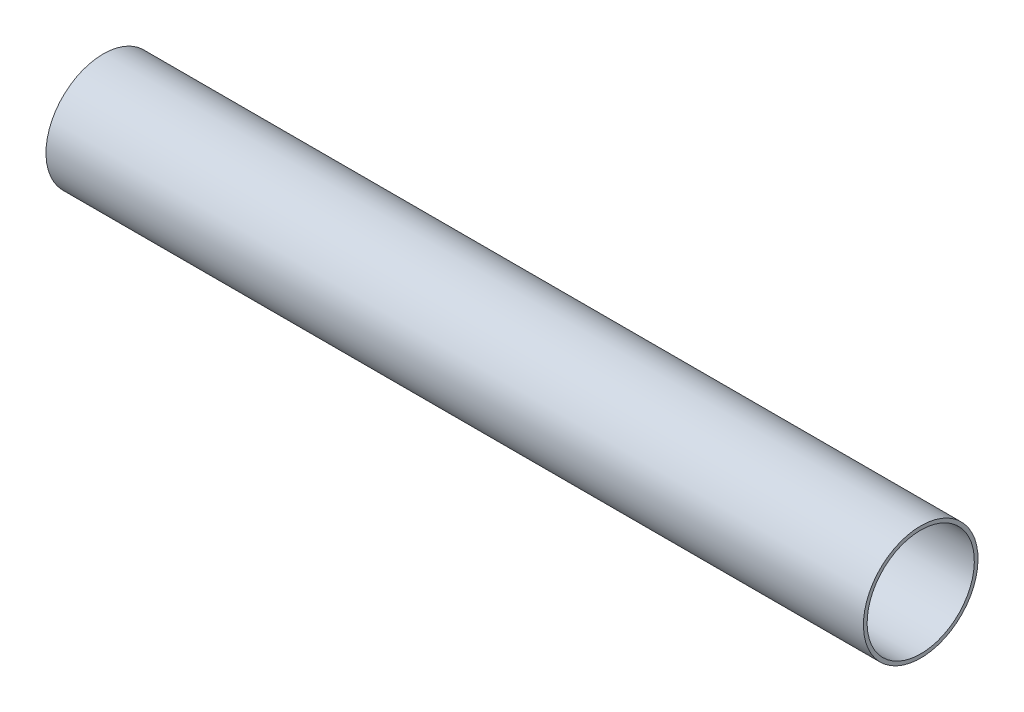
SolidWorks part; units mm, degrees
material "1060 Alloy"
ref_plane "Front Plane" through (0, 0, 0) normal (0, 0, 1) x (1, 0, 0)
ref_plane "Top Plane" through (0, 0, 0) normal (0, 1, 0) x (1, 0, 0)
ref_plane "Right Plane" through (0, 0, 0) normal (1, 0, 0) x (0, 0, -1)
sketch "Sketch1" plane through (0, 0, 0) normal (0, 0, 1) x (1, 0, 0)
  line L1 (0, 0) -> (-702.056, 0) construction
  line L2 (0, 0) -> (0, 49.2125) construction
  line L3 (0, 49.2125) -> (-702.056, 49.2125) construction
  line L4 (-702.056, 0) -> (-702.056, 49.2125) construction
  line L5 (-702.056, 49.2125) -> (0, 49.2125)
  line L6 (-702.056, 49.2125) -> (-702.056, 46.0375)
  line L7 (-702.056, 46.0375) -> (0, 46.0375)
  line L8 (0, 49.2125) -> (0, 46.0375)
  dimension "D1" = 49.2125
  dimension "D2" = 702.056
  dimension "D3" = 3.175
revolve "Revolve1" add sketch "Sketch1" angle 360 about L1
